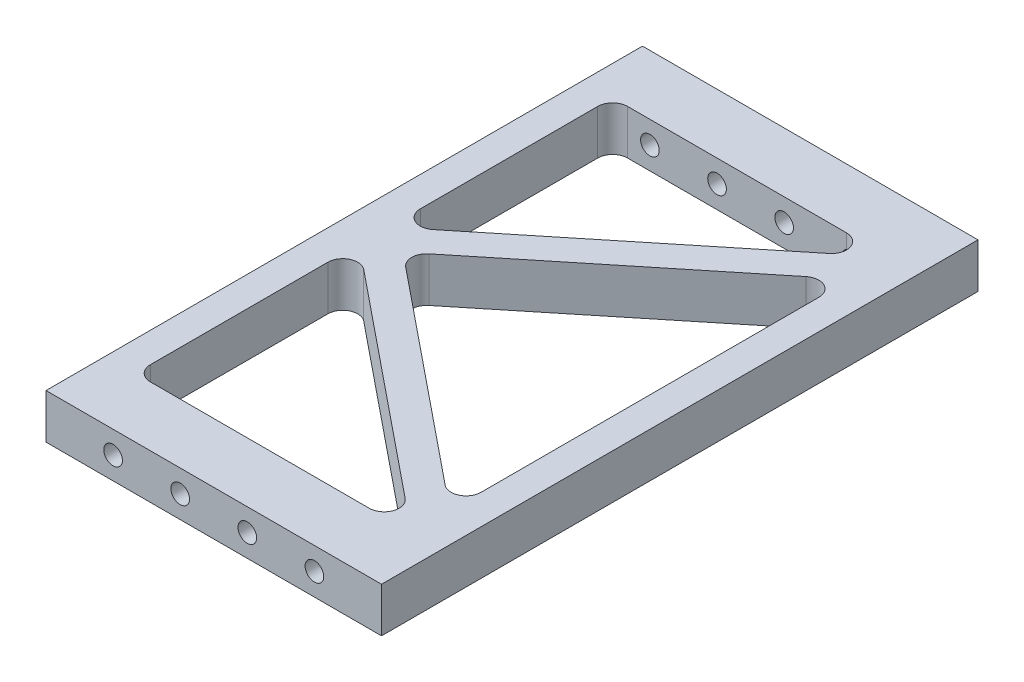
SolidWorks part; units mm, degrees
material "Сплав 2024"
ref_plane "Спереди" through (0, 0, 0) normal (0, 0, 1) x (1, 0, 0)
ref_plane "Сверху" through (0, 0, 0) normal (0, 1, 0) x (1, 0, 0)
ref_plane "Справа" through (0, 0, 0) normal (1, 0, 0) x (0, 0, -1)
sketch "Эскиз1" plane through (0, 0, 0) normal (0, 1, 0) x (1, 0, 0)
  line L2 (-15.9099, 15.9099) -> (15.9099, -15.9099) construction
  line L3 (15.9099, 15.9099) -> (-15.9099, -15.9099) construction
  line L4 (-22.5, 0) -> (-22.5, -80)
  line L5 (-22.5, -80) -> (22.5, -80)
  line L6 (22.5, 0) -> (22.5, -80)
  line L7 (-22.5, 0) -> (22.5, 0)
  dimension "D1" = 80
  dimension "D2" = 45
  dimension "D3" = 45
extrude "Бобышка-Вытянуть1" add sketch "Эскиз1" along normal blind 6
sketch "Эскиз2" plane through (0, 6, 0) normal (0, 1, 0) x (1, 0, 0)
  line L2 (0, 0) -> (0, -80) construction
  line L3 (-22.5, -80) -> (22.5, -80) construction
  line L4 (-12.3744, -52.3744) -> (12.3744, -27.6256) construction
  line L5 (-12.3744, 10) -> (-12.3744, -90) construction
  line L6 (-10.2744, 10) -> (-10.2744, -90)
  line L7 (-14.4744, 10) -> (-14.4744, -90)
  line L8 (-12.3744, -27.6256) -> (12.3744, -52.3744) construction
  line L9 (12.3744, 10) -> (12.3744, -90) construction
  line L10 (10.2744, 10) -> (10.2744, -90)
  line L11 (14.4744, 10) -> (14.4744, -90)
  line L13 (-22.5, -40) -> (22.5, -40) construction
  line L14 (-22.5, 0) -> (-22.5, -80) construction
  line L15 (22.5, -80) -> (22.5, 0) construction
  circle A0 centre (0, -40) radius 6 construction
  circle A1 centre (0, -40) radius 17.5 construction
  arc A2 (-10.2744, 10) -> (-14.4744, 10) centre (-12.3744, 10) ccw
  arc A3 (-14.4744, -90) -> (-10.2744, -90) centre (-12.3744, -90) ccw
  arc A4 (10.2744, 10) -> (14.4744, 10) centre (12.3744, 10) cw
  arc A5 (14.4744, -90) -> (10.2744, -90) centre (12.3744, -90) cw
  point P13 (12.3744, -40)
  point P18 (-12.3744, -40)
  point P37 (0, -123.5)
  dimension "D1" = 12
  dimension "D2" = 35
  dimension "D4" = 2.1
  dimension "D3" = 45
  dimension "D5" = 100
hole_wizard "Цековка для  винта с полукруглой головкой M31" [suppressed] positions "Эскиз4" profile "Эскиз5" counterbore size "M3" standard "Ansi Metric"
sketch "Эскиз4" plane through (0, 6, 0) normal (0, 1, 0) x (1, 0, 0)
  line L2 (-36.6046, 36.6046) -> (36.6046, -36.6046) construction
  line L3 (-12.3744, -12.3744) -> (12.3744, 12.3744) construction
  circle A0 centre (0, 0) radius 6 construction
  point P0 (-4.2426, 4.2426)
  point P6 (-4.2426, -4.2426)
  point P10 (4.2426, -4.2426)
  point P12 (4.2426, 4.2426)
sketch "Эскиз5" plane through (-4.2426, 6, -4.2426) normal (1, 0, 0) x (0, 0, 1)
  line L0 (0, 0) -> (0, 6)
  line L1 (0, 6) -> (1.7, 6)
  line L3 (1.7, 6) -> (1.7, 2)
  line L4 (1.7, 2) -> (3.35, 2)
  line L5 (3.35, 2) -> (3.35, 0)
  line L7 (3.35, 0) -> (0, 0)
  line L11 (0, -6.35) -> (0, 107.95) construction
  dimension "Диаметр сквозного отверстия" = 3.4
  dimension "Глубина сквозного отверстия" = 6
  dimension "Диаметр цековки" = 6.7
  dimension "Глубина цековки" = 2
hole_wizard "Отверстие обработанное метчиком M4x0.71" [suppressed] positions "Эскиз7" profile "Эскиз6" tap size "M4x0.7" standard "Ansi Metric"
sketch "Эскиз7" [suppressed] plane through (0, 4, 0) normal (0, 1, 0) x (1, 0, 0)
  line L0 (22.5, 0) -> (-22.5, 0) construction
  line L1 (0, 22.5) -> (0, -22.5) construction
  circle A0 centre (0, 0) radius 19.25 construction
  point P0 (-19.25, 0)
  point P6 (0, -19.25)
  point P10 (19.25, 0)
  point P12 (0, 19.25)
sketch "Эскиз6" plane through (-19.25, 4, 0) normal (1, 0, 0) x (0, 0, 1)
  line L0 (0, 0) -> (0, 4)
  line L1 (0, 4) -> (1.65, 4)
  line L2 (1.65, 4) -> (1.65, 0)
  line L5 (1.65, 0) -> (0, 0)
  line L11 (0, -6.35) -> (0, 107.95) construction
  dimension "Диаметр резьбы" = 3.3
  dimension "Глубина проходного сверла" = 4
extrude "Вырез-Вытянуть1" [suppressed] cut sketch "Эскиз2" against normal through all
sketch "Эскиз8" plane through (0, 0, 80) normal (0, 0, 1) x (1, 0, 0)
  line L0 (-22.5, 3) -> (22.5, 3) construction
  line L1 (-22.5, 6) -> (-22.5, 0) construction
  line L2 (22.5, 6) -> (22.5, 0) construction
  line L3 (-13.5, 6) -> (-13.5, 0) construction
  line L6 (-4.5, 6) -> (-4.5, 0) construction
  line L7 (4.5, 6) -> (4.5, 0) construction
  line L8 (13.5, 6) -> (13.5, 0) construction
  dimension "D1" = 45
  dimension "D2" = 9
  dimension "D3" = 9
  dimension "D4" = 9
  dimension "D5" = 9
sketch "Эскиз13" plane through (0, 6, 0) normal (0, 1, 0) x (1, 0, 0)
  line L0 (-18.5, 0) -> (-18.5, -80) construction
  line L1 (22.5, 0) -> (-22.5, 0) construction
  line L2 (-22.5, -80) -> (22.5, -80) construction
  line L3 (18.5, 0) -> (18.5, -80) construction
  line L4 (-22.5, -72) -> (22.5, -72) construction
  line L5 (-22.5, 0) -> (-22.5, -80) construction
  line L6 (22.5, -80) -> (22.5, 0) construction
  line L7 (-22.5, -8) -> (22.5, -8) construction
  line L8 (22.5, -4.7568) -> (-18.7822, -38.2288) construction
  line L9 (-32.8409, -30.3722) -> (17.7355, -71.3801) construction
  line L10 (-18.5, -8) -> (18.5, -8)
  line L11 (-26.2522, -38) -> (27.2799, -38) construction
  line L12 (-24.8337, -42) -> (28.2346, -42) construction
  line L13 (18.5, -40) -> (-22.5, -40) construction
  line L14 (18.5, -8) -> (-18.5, -38)
  line L15 (-18.5, -38) -> (-18.5, -8)
  line L16 (18.5, -72) -> (-18.5, -42)
  line L17 (-18.5, -42) -> (-18.5, -72)
  line L18 (-18.5, -72) -> (18.5, -72)
  line L19 (18.5, -13.1496) -> (-14.6155, -40)
  line L20 (18.5, -66.8504) -> (-14.6155, -40)
  line L21 (18.5, -13.1496) -> (18.5, -66.8504)
  point P16 (18.5, -72)
  point P32 (-18.5, -42)
  dimension "D1" = 4
  dimension "D2" = 4
  dimension "D3" = 8
  dimension "D4" = 8
  dimension "D5" = 2
  dimension "D6" = 2
  dimension "D7" = 4
extrude "Вырез-Вытянуть2" cut sketch "Эскиз13" against normal through all
fillet "Скругление10" radius 2 9 edges at (-14.6155, 3, 40) (18.5, 3, 13.1496) (18.5, 3, 66.8504) (18.5, 3, 72) (-18.5, 3, 72) (-18.5, 3, 42) (18.5, 3, 8) (-18.5, 3, 8) (-18.5, 3, 38)
chamfer "Фаска1" [suppressed] distance 1 angle 45
hole_wizard "Отверстие обработанное метчиком M3x0.52" positions "Эскиз12" profile "Эскиз11" tap size "M3x0.5" standard "Ansi Metric"
sketch "Эскиз12" plane through (0, 0, 0) normal (0, 0, -1) x (-1, 0, 0)
  line L0 (-13.5, 6) -> (-13.5, 0) construction
  line L1 (-4.5, 6) -> (-4.5, 0) construction
  line L2 (4.5, 6) -> (4.5, 0) construction
  line L3 (13.5, 6) -> (13.5, 0) construction
  point P0 (-13.5, 3)
  point P4 (-4.5, 3)
  point P8 (4.5, 3)
  point P12 (13.5, 3)
sketch "Эскиз11" plane through (13.5, 3, 0) normal (1, 0, 0) x (0, 1, 0)
  line L0 (0, 0) -> (0, 9.2511)
  line L1 (0, 9.2511) -> (1.25, 8.5)
  line L2 (1.25, 8.5) -> (1.25, 0)
  line L5 (1.25, 0) -> (0, 0)
  line L10 (0, 9.2511) -> (-1.25, 8.5) construction
  line L11 (0, -6.35) -> (0, 107.95) construction
  dimension "Диаметр сверла" = 2.5
  dimension "Глубина сверла" = 8.5
  dimension "Угол заточки сверла" = 118
cosmetic thread "Отверстие резьбы5" parameters "D1"=6, "D2"=3
cosmetic thread "Отверстие резьбы6" parameters "D1"=6, "D2"=3
cosmetic thread "Отверстие резьбы7" parameters "D1"=6, "D2"=3
cosmetic thread "Отверстие резьбы8" parameters "D1"=6, "D2"=3
hole_wizard "Отверстие обработанное метчиком M3x0.51" positions "Эскиз10" profile "Эскиз9" tap size "M3x0.5" standard "Ansi Metric"
sketch "Эскиз10" plane through (0, 0, 80) normal (0, 0, 1) x (1, 0, 0)
  line L0 (-13.5, 6) -> (-13.5, 0) construction
  line L1 (-4.5, 6) -> (-4.5, 0) construction
  line L2 (4.5, 6) -> (4.5, 0) construction
  line L3 (13.5, 6) -> (13.5, 0) construction
  point P0 (-13.5, 3)
  point P4 (-4.5, 3)
  point P8 (4.5, 3)
  point P12 (13.5, 3)
sketch "Эскиз9" plane through (-13.5, 3, 80) normal (1, 0, 0) x (0, -1, 0)
  line L0 (0, 0) -> (0, 9.2511)
  line L1 (0, 9.2511) -> (1.25, 8.5)
  line L2 (1.25, 8.5) -> (1.25, 0)
  line L5 (1.25, 0) -> (0, 0)
  line L10 (0, 9.2511) -> (-1.25, 8.5) construction
  line L11 (0, -6.35) -> (0, 107.95) construction
  dimension "Диаметр сверла" = 2.5
  dimension "Глубина сверла" = 8.5
  dimension "Угол заточки сверла" = 118
cosmetic thread "Отверстие резьбы1" parameters "D1"=6, "D2"=3
cosmetic thread "Отверстие резьбы2" parameters "D1"=6, "D2"=3
cosmetic thread "Отверстие резьбы3" parameters "D1"=6, "D2"=3
cosmetic thread "Отверстие резьбы4" parameters "D1"=6, "D2"=3
equation "\"D2@Эскиз8\"=\"D1@Эскиз8\"/5"
equation "\"D3@Эскиз8\"=\"D2@Эскиз8\""
equation "\"D4@Эскиз8\"=\"D2@Эскиз8\""
equation "\"D5@Эскиз8\"=\"D2@Эскиз8\""
